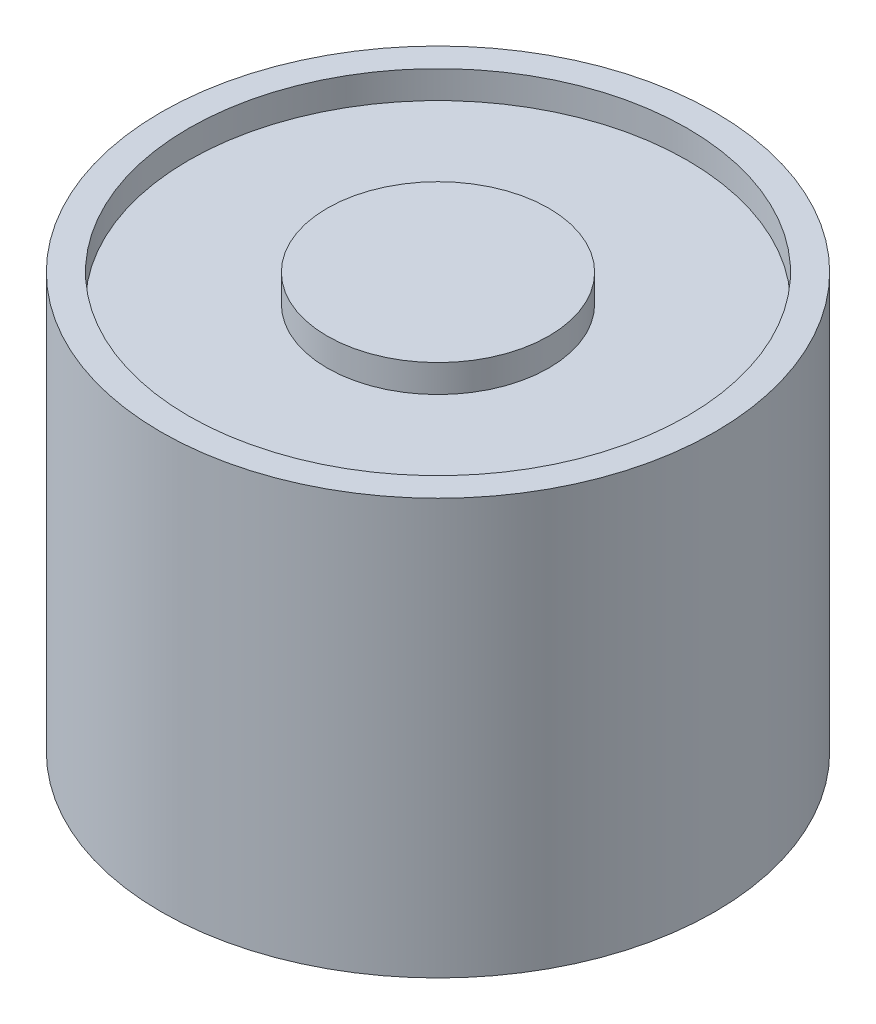
SolidWorks part; units mm, degrees
ref_plane "Front Plane" through (0, 0, 0) normal (0, 0, 1) x (1, 0, 0)
ref_plane "Top Plane" through (0, 0, 0) normal (0, 1, 0) x (1, 0, 0)
ref_plane "Right Plane" through (0, 0, 0) normal (1, 0, 0) x (0, 0, -1)
sketch "Sketch1" plane through (0, 0, 0) normal (0, 1, 0) x (1, 0, 0)
  circle A0 centre (0, 0) radius 10
extrude "Boss-Extrude1" add sketch "Sketch1" along normal blind 15
sketch "Sketch2" plane through (0, 15, 0) normal (0, 1, 0) x (1, 0, 0)
  line L0 (-10, 0) -> (10, 0) construction
  circle A0 centre (0, 0) radius 10 construction
  circle A1 centre (0, 0) radius 4
  circle A2 centre (0, 0) radius 9
  point P7 (0, 0)
extrude "Cut-Extrude1" cut sketch "Sketch2" against normal blind 1
hole_wizard "M3 Clearance Hole1" positions "Sketch4" profile "Sketch5" hole size "M3" standard "AS"
sketch "Sketch4" plane through (0, 0, 0) normal (0, -1, 0) x (-1, 0, 0)
  point P0 (0, 0)
sketch "Sketch5" plane through (0, 0, 0) normal (1, 0, 0) x (0, 0, -1)
  line L0 (0, 0) -> (0, 5.9614)
  line L1 (0, 5.9614) -> (1.6, 5)
  line L2 (1.6, 5) -> (1.6, 0)
  line L5 (1.6, 0) -> (0, 0)
  line L10 (0, 5.9614) -> (-1.6, 5) construction
  line L11 (0, -6.35) -> (0, 107.95) construction
  dimension "Hole Dia." = 3.2
  dimension "Hole Depth" = 5
  dimension "Drill Angle" = 118
